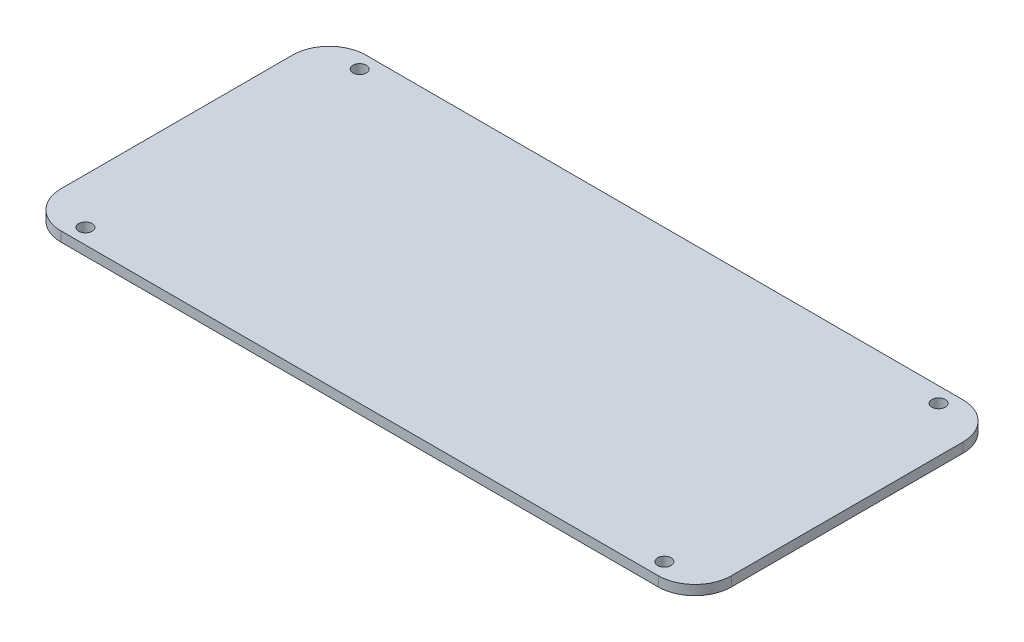
SolidWorks part; units mm, degrees
ref_plane "Ebene vorne" through (0, 0, 0) normal (0, 0, 1) x (1, 0, 0)
ref_plane "Ebene oben" through (0, 0, 0) normal (0, 1, 0) x (1, 0, 0)
ref_plane "Ebene rechts" through (0, 0, 0) normal (1, 0, 0) x (0, 0, -1)
sketch "Skizze1" plane through (0, 0, 0) normal (0, 1, 0) x (1, 0, 0)
  line L13 (-49, 25) -> (49, 25)
  line L14 (-55, 19) -> (-55, -19)
  line L15 (-49, -25) -> (49, -25)
  line L16 (55, 19) -> (55, -19)
  line L17 (-55, 25) -> (55, -25) construction
  line L18 (-55, -25) -> (55, 25) construction
  circle A0 centre (47.5, 22.5) radius 1.1
  circle A1 centre (-47.5, 22.5) radius 1.1
  circle A2 centre (47.5, -22.5) radius 1.1
  circle A3 centre (-47.5, -22.5) radius 1.1
  arc A4 (49, 25) -> (55, 19) centre (49, 19) cw
  arc A5 (49, -25) -> (55, -19) centre (49, -19) ccw
  arc A6 (-55, -19) -> (-49, -25) centre (-49, -19) ccw
  arc A7 (-49, 25) -> (-55, 19) centre (-49, 19) ccw
  point P0 (0, 0)
  point P17 (0, 0)
  dimension "D8" = 2.2
  dimension "D1" = 6
  dimension "D3" = 7.5
  dimension "D4" = 110
  dimension "D5" = 50
  dimension "D6" = 7.5
  dimension "D7" = 2.5
  dimension "D9" = 2.5
extrude "Aufsatz-Linear austragen1" add sketch "Skizze1" along normal blind 1.6
